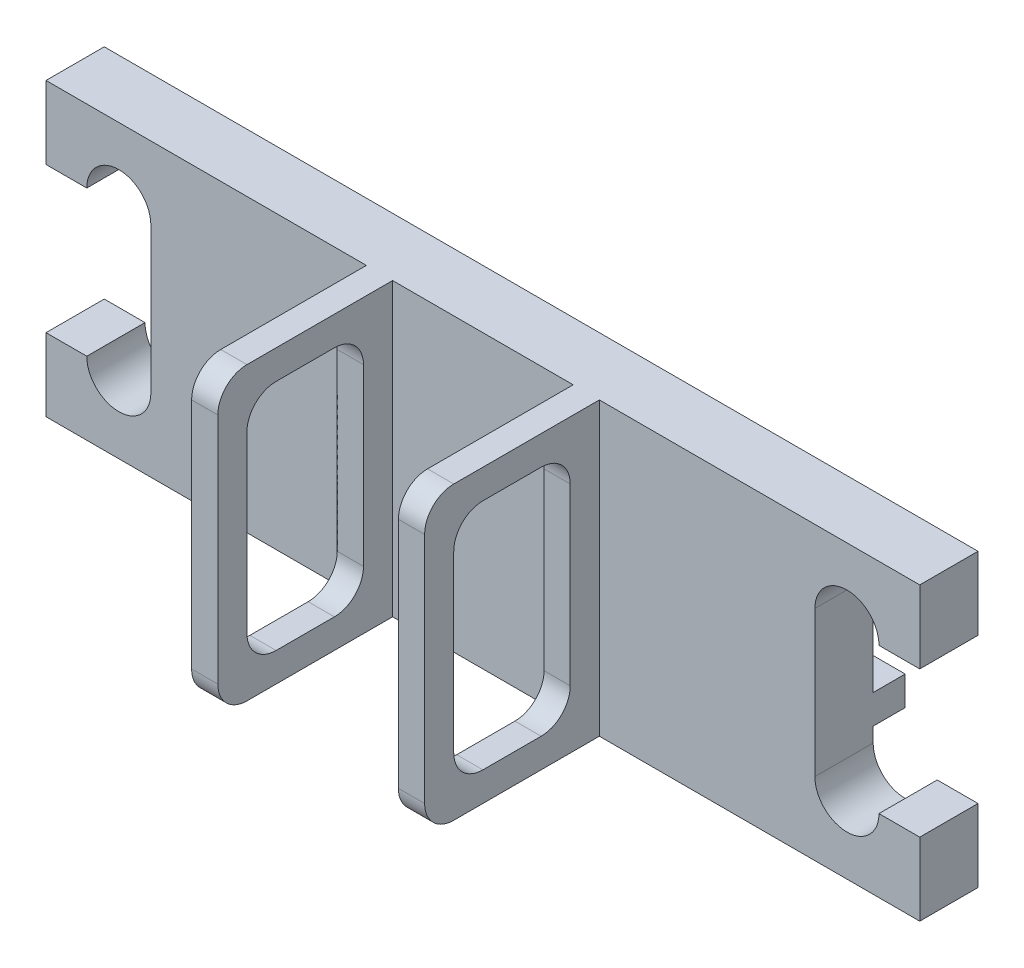
SolidWorks part; units mm, degrees
ref_plane "Alzado" through (0, 0, 0) normal (0, 0, 1) x (1, 0, 0)
ref_plane "Planta" through (0, 0, 0) normal (0, 1, 0) x (1, 0, 0)
ref_plane "Vista lateral" through (0, 0, 0) normal (1, 0, 0) x (0, 0, -1)
sketch "Croquis1" plane through (0, 0, 0) normal (0, 0, 1) x (1, 0, 0)
  line L1 (-15, 5) -> (15, 5)
  line L2 (-15, 5) -> (-15, -5)
  line L3 (-15, -5) -> (15, -5)
  line L4 (15, 5) -> (15, -5)
  line L5 (-15, 5) -> (15, -5) construction
  line L6 (-15, -5) -> (15, 5) construction
  point P0 (0, 0)
  dimension "D1" = 30
  dimension "D2" = 10
extrude "Saliente-Extruir1" add sketch "Croquis1" along normal blind 2
sketch "Croquis2" plane through (0, 0, 2) normal (0, 0, 1) x (1, 0, 0)
  line L0 (-11.5, 0) -> (11.5, 0)
  line L2 (11.5, 2.5) -> (11.5, -2.5)
  line L3 (13.5, 2.5) -> (13.5, -2.5)
  line L4 (-11.5, -2.5) -> (-11.5, 2.5)
  line L5 (-13.5, -2.5) -> (-13.5, 2.5)
  arc A1 (-11.5, 2.5) -> (-13.5, 2.5) centre (-12.5, 2.5) ccw
  arc A2 (-13.5, -2.5) -> (-11.5, -2.5) centre (-12.5, -2.5) ccw
  arc A3 (13.5, 2.5) -> (11.5, 2.5) centre (12.5, 2.5) ccw
  arc A4 (11.5, -2.5) -> (13.5, -2.5) centre (12.5, -2.5) ccw
  point P4 (0, 0)
  point P10 (-12.5, 0)
  dimension "D3" = 5
extrude "Cortar-Extruir2" cut sketch "Croquis2" against normal blind 11 contours L5 A2 L4 A1 | L2 A4 L3 A3
sketch "Croquis3" plane through (0, 0, 0) normal (0, 0, -1) x (-1, 0, 0)
  line L0 (-10.8877, -2.5) -> (11.5, -2.5)
  line L1 (0.3062, -2.5) -> (0.3062, -0.5) construction
  line L2 (0.3062, -1) -> (0.3062, -2)
  line L3 (-11.5, -2) -> (-11.5, -1)
  line L4 (-11.5, 2.5) -> (-11.5, -2.5) construction
  line L5 (-11.5, -1) -> (11.5, -1)
  line L6 (11.5, -2.5) -> (11.5, 2.5) construction
  line L7 (11.5, -1) -> (11.5, -2)
  line L8 (11.5, -2) -> (-11.5, -2)
  point P8 (0.3062, -1.5)
  line M8 (-11.5, 2.5) -> (-11.5, -2.5)
  line M13 (11.5, -2.5) -> (11.5, 2.5)
  dimension "D1" = 2
  dimension "D2" = 1
extrude "Saliente-Extruir3" add sketch "Croquis3" along normal blind 1.5 contours L8 L5 L2 M13 | L8 L2 L5 M8
sketch "Croquis4" plane through (0, 0, 2) normal (0, 0, 1) x (1, 0, 0)
  line L0 (-12.5, 3.5) -> (-12.5, 3.6) construction
  line L1 (-12.5, -3.5) -> (-12.5, -3.6) construction
  line L2 (-13.5, 0) -> (-13.6, 0) construction
  line L3 (-13.5, -2.5) -> (-13.5, 2.5) construction
  line L4 (-11.5, 0) -> (-11.4, 0) construction
  line L5 (-11.5, -2.5) -> (-11.5, 2.5) construction
  line L6 (12.5, 3.5) -> (12.5, 3.6) construction
  line L7 (12.5, -3.5) -> (12.5, -3.6) construction
  line L8 (-13.6, 2.5) -> (-13.6, -2.5)
  line L9 (-11.4, 2.5) -> (-11.4, -2.5)
  line L10 (11.4, 2.5) -> (11.4, -2.5)
  line L11 (13.6, 2.5) -> (13.6, -2.5)
  arc A0 (-11.5, 2.5) -> (-13.5, 2.5) centre (-12.5, 2.5) ccw construction
  arc A1 (-13.5, -2.5) -> (-11.5, -2.5) centre (-12.5, -2.5) ccw construction
  arc A2 (-11.4, 2.5) -> (-13.6, 2.5) centre (-12.5, 2.5) ccw
  arc A3 (-13.6, -2.5) -> (-11.4, -2.5) centre (-12.5, -2.5) ccw
  arc A4 (13.5, 2.5) -> (11.5, 2.5) centre (12.5, 2.5) ccw construction
  arc A5 (11.5, -2.5) -> (13.5, -2.5) centre (12.5, -2.5) ccw construction
  arc A6 (11.4, -2.5) -> (13.6, -2.5) centre (12.5, -2.5) ccw
  arc A7 (13.6, 2.5) -> (11.4, 2.5) centre (12.5, 2.5) ccw
  dimension "D1" = 0.1
  dimension "D2" = 0.1
  dimension "D3" = 0.1
  dimension "D4" = 0.1
  dimension "D5" = 0.1
  dimension "D6" = 0.1
extrude "Cortar-Extruir3" cut sketch "Croquis4" against normal blind 11.5 contours A3 L9 A2 L8 | A7 L10 A6 L11
sketch "Croquis5" plane through (0, 0, 2) normal (0, 0, 1) x (1, 0, 0)
  line L0 (-15, 5) -> (-15, -5) construction
  line L1 (-13.6, 2.5) -> (-15, 2.5)
  line L2 (-13.6, 2.5) -> (-13.6, -2.5)
  line L3 (-13.6, -2.5) -> (-15, -2.5)
  line L4 (-15, 2.5) -> (-15, -2.5)
  line L5 (15, -5) -> (15, 5) construction
  line L6 (13.6, 2.5) -> (15, 2.5)
  line L7 (13.6, 2.5) -> (13.6, -2.5)
  line L8 (13.6, -2.5) -> (15, -2.5)
  line L9 (15, 2.5) -> (15, -2.5)
  arc A0 (-11.4, 2.5) -> (-13.6, 2.5) centre (-12.5, 2.5) ccw construction
extrude "Cortar-Extruir4" cut sketch "Croquis5" against normal blind 10
sketch "Croquis6" plane through (0, 0, 2) normal (0, 0, 1) x (1, 0, 0)
  line L0 (-4, 0) -> (4, 0)
  line L1 (15, 5) -> (-15, 5) construction
  line L2 (-4, 5) -> (4, 5)
  line L3 (-4, 5) -> (-4, -5)
  line L4 (-4, -5) -> (4, -5)
  line L5 (4, 5) -> (4, -5)
  line L6 (-15, -5) -> (15, -5) construction
  point P4 (0, 0)
  line M4 (-15, -5) -> (15, -5)
  line M12 (15, 5) -> (-15, 5)
  dimension "D1" = 8
extrude "Saliente-Extruir4" add sketch "Croquis6" along normal blind 6 contours L5 L3 L0 M12 | L5 L0 L3 M4
sketch "Croquis7" plane through (0, 5, 0) normal (0, 1, 0) x (1, 0, 0)
  line L0 (-4, -2) -> (4, -2) construction
  line L1 (0, -2) -> (0, -8) construction
  line L2 (4, -8) -> (-4, -8) construction
  line L4 (-3.1, -2) -> (3.1, -2)
  line L5 (-3.1, -2) -> (-3.1, -8)
  line L6 (-3.1, -8) -> (3.1, -8)
  line L7 (3.1, -2) -> (3.1, -8)
  line L8 (-3.1, -2) -> (3.1, -8) construction
  line L9 (-3.1, -8) -> (3.1, -2) construction
  point P8 (0, -5)
  dimension "D1" = 6.2
extrude "Cortar-Extruir5" cut sketch "Croquis7" against normal blind 11
sketch "Croquis8" plane through (-4, 0, 0) normal (-1, 0, 0) x (0, 0, 1)
  line L0 (2, 0) -> (8, 0) construction
  line L1 (2, 5) -> (2, -5) construction
  line L2 (8, 5) -> (8, -5) construction
  line L3 (5, 5) -> (5, -5)
  line L4 (8, -5) -> (2, -5) construction
  line L6 (4, 4) -> (6, 4)
  line L7 (3, 3) -> (3, -3)
  line L8 (4, -4) -> (6, -4)
  line L9 (7, 3) -> (7, -3)
  line L10 (3, 4) -> (7, -4) construction
  line L11 (3, -4) -> (7, 4) construction
  arc A0 (3, -3) -> (4, -4) centre (4, -3) ccw
  arc A1 (6, -4) -> (7, -3) centre (6, -3) ccw
  arc A2 (6, 4) -> (7, 3) centre (6, 3) cw
  arc A3 (4, 4) -> (3, 3) centre (4, 3) ccw
  point P6 (5, 0)
  point P11 (5, 0)
  dimension "D3" = 1
  dimension "D1" = 8
  dimension "D2" = 4
extrude "Cortar-Extruir6" cut sketch "Croquis8" against normal blind 11 contours L6 A3 L7 A0 L8 L3 | A2 L6 L3 L8 A1 L9
fillet "Redondeo1" radius 1 2 edges at (3.55, -5, 8) (3.55, 5, 8)
sketch "Croquis9" plane through (11.4, 0, 0) normal (1, 0, 0) x (0, 0, -1)
  line L0 (0, -2) -> (1.5, -2) construction
  line L1 (1.5, -1) -> (1.1, -1)
  line L2 (1.5, -1) -> (1.5, -2)
  line L3 (1.5, -2) -> (1.1, -2)
  line L4 (1.1, -1) -> (1.1, -2)
  dimension "D1" = 0.4
extrude "Cortar-Extruir7" cut sketch "Croquis9" against normal blind 23
